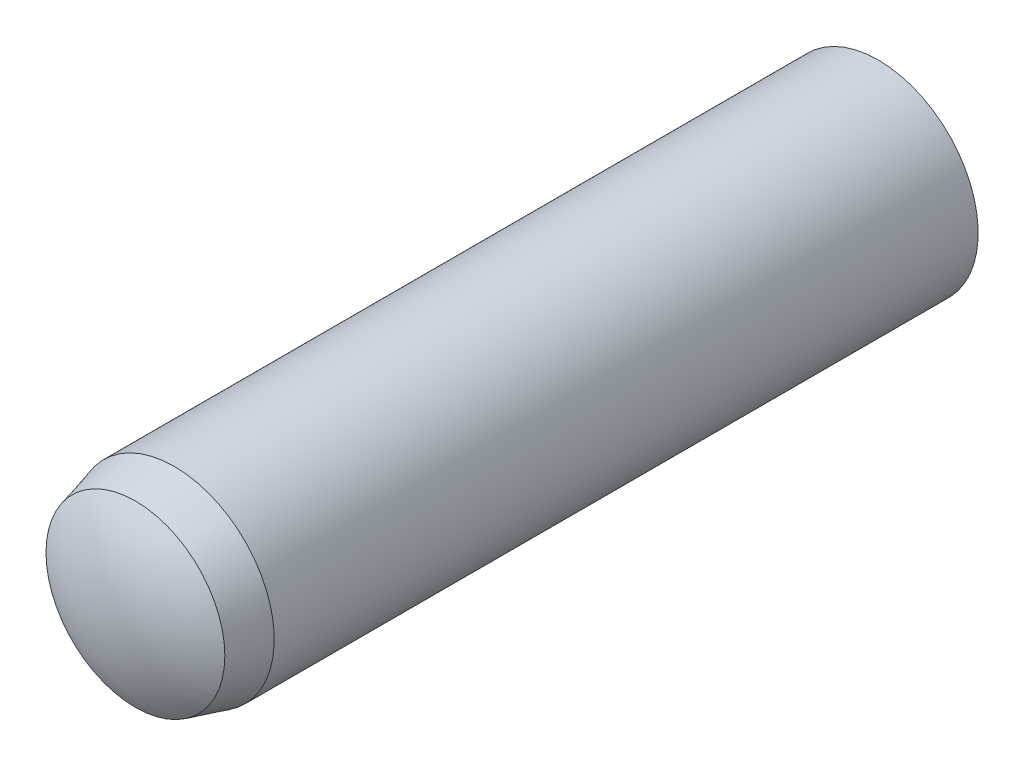
SolidWorks part; units mm, degrees
ref_plane "Front Plane" through (0, 0, 0) normal (0, 0, 1) x (1, 0, 0)
ref_plane "Top Plane" through (0, 0, 0) normal (0, 1, 0) x (1, 0, 0)
ref_plane "Right Plane" through (0, 0, 0) normal (1, 0, 0) x (0, 0, -1)
sketch "Sketch1" plane through (0, 0, 0) normal (0, 0, 1) x (1, 0, 0)
  circle A0 centre (0, 0) radius 2.5
  point P3 (0, 2.5)
  dimension "Diameter" = 5
sketch "Sketch2" plane through (0, 0, 0) normal (1, 0, 0) x (0, 0, -1)
  line L0 (-10, 0) -> (10, 0) construction
  line L1 (-10, 0) -> (-10, 2.5) construction
  line L2 (-10, 2.5) -> (10, 2.5)
  line L3 (10, 2.5) -> (10, 0) construction
  line L4 (-9.35, 2.2387) -> (-8.375, 2.5)
  arc A0 (-10, 0) -> (-9.35, 2.2387) centre (-5.8196, 0) cw
  arc A1 (10, 0) -> (9.25, 2.5) centre (5.4583, 0) ccw
  point P2 (0, 0)
  point P11 (-5, 0)
  point P13 (5, 0)
  dimension "Length" = 20
  dimension "D1" = 15
  dimension "D2" = 0.75
  dimension "D3" = 1.625
  dimension "D4" = 0.975
  dimension "D5" = 5
  dimension "D6" = 5
sketch "Sketch3" plane through (0, 0, 0) normal (1, 0, 0) x (0, 0, -1)
  line L0 (-10, 0) -> (10, 0) construction
  line L1 (-9.35, 2.2387) -> (-8.375, 2.5) construction
  line L2 (-10, 0) -> (10, 0)
  line L3 (-9.35, 2.2387) -> (-8.375, 2.5)
  line L4 (-8.375, 2.5) -> (9.25, 2.5)
  arc A0 (10, 0) -> (9.25, 2.5) centre (5.4583, 0) ccw construction
  arc A1 (-9.35, 2.2387) -> (-10, 0) centre (-5.8196, 0) ccw construction
  arc A2 (10, 0) -> (9.25, 2.5) centre (5.4583, 0) ccw
  arc A3 (-9.35, 2.2387) -> (-10, 0) centre (-5.8196, 0) ccw
revolve "Revolve1" add sketch "Sketch3" angle 360 about L2
equation "\"D2@Sketch2\" = \"Diameter@Sketch1\" * .15"
equation "\"D3@Sketch2\" = \"Diameter@Sketch1\" * .325"
equation "\"D4@Sketch2\" = \"D3@Sketch2\" * .6"
equation "\"D5@Sketch2\"=\"Diameter@Sketch1\""
equation "\"D6@Sketch2\"=\"D5@sketch2\""
